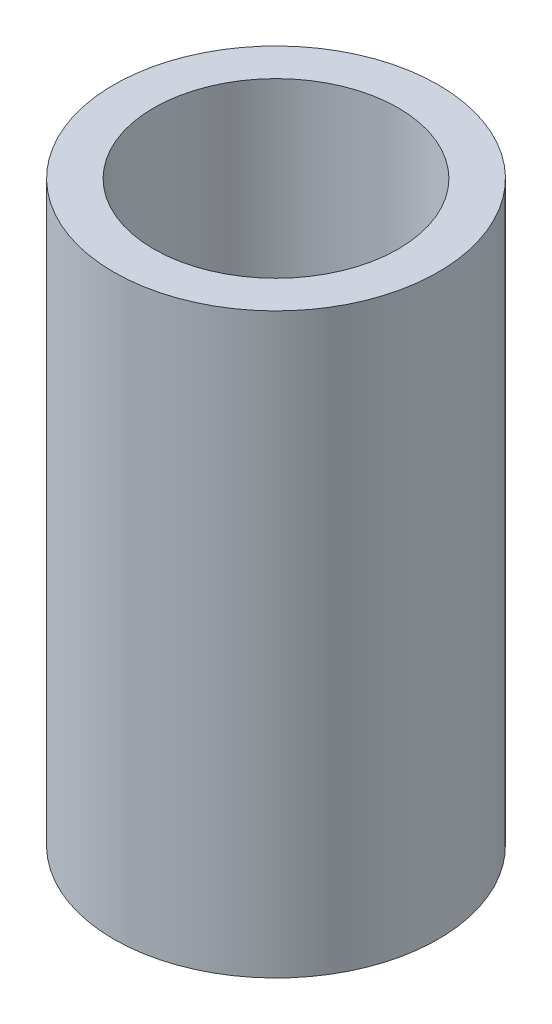
SolidWorks part; units mm, degrees
ref_plane "Płaszczyzna przednia" through (0, 0, 0) normal (0, 0, 1) x (1, 0, 0)
ref_plane "Płaszczyzna górna" through (0, 0, 0) normal (0, 1, 0) x (1, 0, 0)
ref_plane "Płaszczyzna prawa" through (0, 0, 0) normal (1, 0, 0) x (0, 0, -1)
sketch "Szkic1" plane through (0, 0, 0) normal (0, 1, 0) x (1, 0, 0)
  circle A0 centre (0, 0) radius 12.7
  circle A1 centre (0, 0) radius 16.85
  dimension "D1" = 25.4
  dimension "D2" = 33.7
extrude "Dodanie-wyciągnięcie1" add sketch "Szkic1" along normal blind 60
